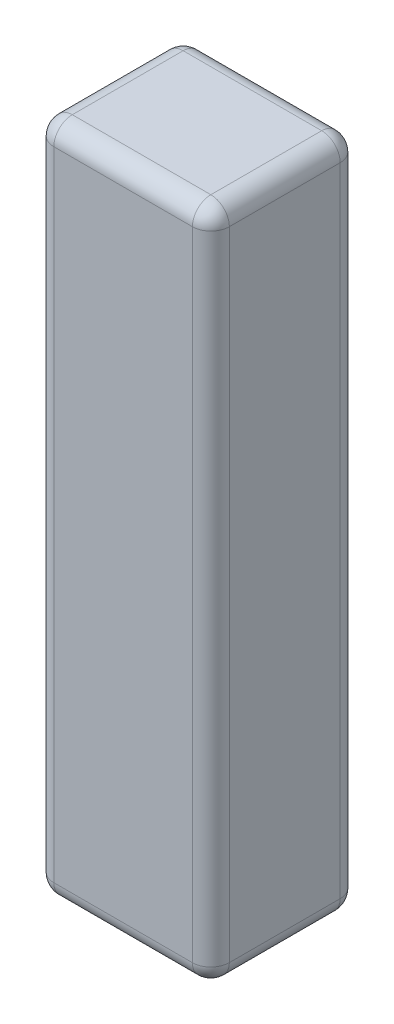
SolidWorks part; units mm, degrees
ref_plane "Front Plane" through (0, 0, 0) normal (0, 0, 1) x (1, 0, 0)
ref_plane "Top Plane" through (0, 0, 0) normal (0, 1, 0) x (1, 0, 0)
ref_plane "Right Plane" through (0, 0, 0) normal (1, 0, 0) x (0, 0, -1)
sketch "Sketch1" plane through (0, 0, 0) normal (0, 1, 0) x (1, 0, 0)
  line L1 (-9.5, -8) -> (9.5, -8)
  line L2 (-9.5, -8) -> (-9.5, 8)
  line L3 (-9.5, 8) -> (9.5, 8)
  line L4 (9.5, -8) -> (9.5, 8)
  line L5 (-9.5, -8) -> (9.5, 8) construction
  line L6 (-9.5, 8) -> (9.5, -8) construction
  point P0 (0, 0)
  dimension "D1" = 16
  dimension "D2" = 19
extrude "Boss-Extrude1" add sketch "Sketch1" along normal blind 73
fillet "Fillet1" radius 2 12 edges at (-9.5, 73, 0) (0, 73, -8) (9.5, 73, 0) (0, 73, 8) (0, 0, 8) (9.5, 0, 0) (-9.5, 0, 0) (0, 0, -8) (-9.5, 36.5, 8) (-9.5, 36.5, -8) (9.5, 36.5, -8) (9.5, 36.5, 8)
